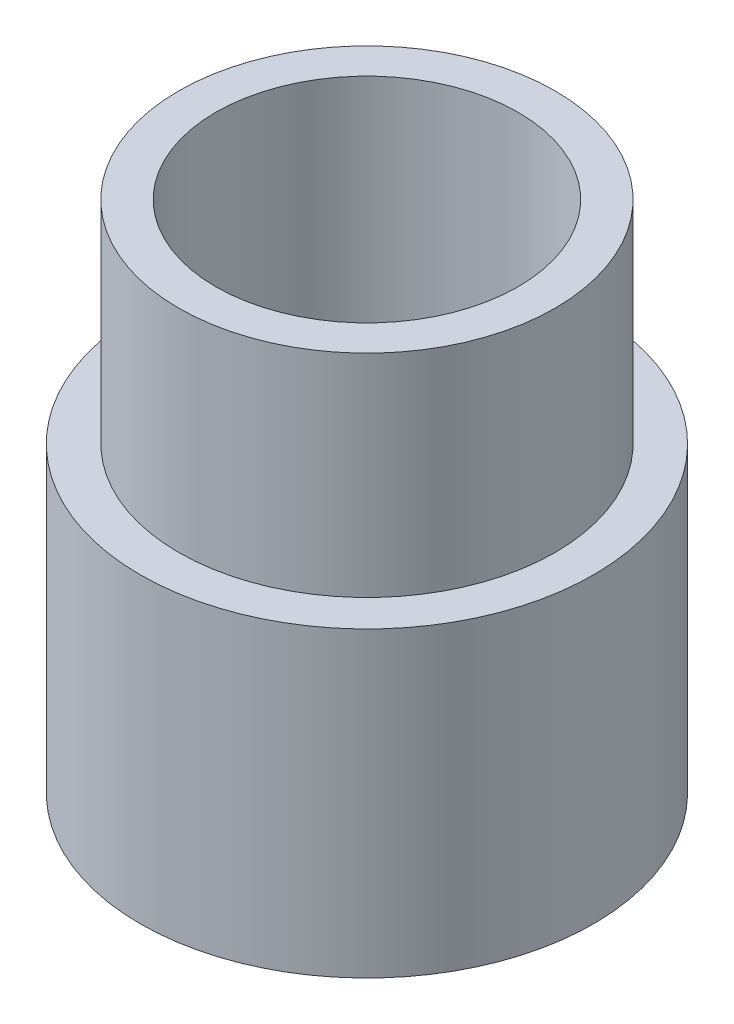
SolidWorks part; units mm, degrees
ref_plane "Front Plane" through (0, 0, 0) normal (0, 0, 1) x (1, 0, 0)
ref_plane "Top Plane" through (0, 0, 0) normal (0, 1, 0) x (1, 0, 0)
ref_plane "Right Plane" through (0, 0, 0) normal (1, 0, 0) x (0, 0, -1)
sketch "Sketch1" plane through (0, 0, 0) normal (0, 1, 0) x (1, 0, 0)
  circle A0 centre (0, 0) radius 7.5
  dimension "D1" = 15
extrude "Boss-Extrude1" add sketch "Sketch1" along normal blind 10
sketch "Sketch2" plane through (0, 0, 0) normal (0, -1, 0) x (1, 0, 0)
  circle A1 centre (0, 0) radius 6.25
  dimension "D1" = 12.5
extrude "Cut-Extrude1" cut sketch "Sketch2" against normal blind 7.5 contours A1
sketch "Sketch3" plane through (0, 10, 0) normal (0, 1, 0) x (1, 0, 0)
  circle A0 centre (0, 0) radius 6.225
  dimension "D1" = 12.45
extrude "Boss-Extrude2" add sketch "Sketch3" along normal blind 7
sketch "Sketch4" plane through (0, 17, 0) normal (0, 1, 0) x (1, 0, 0)
  circle A0 centre (0, 0) radius 5
  dimension "D1" = 10
extrude "Cut-Extrude3" cut sketch "Sketch4" against normal blind 10.5
